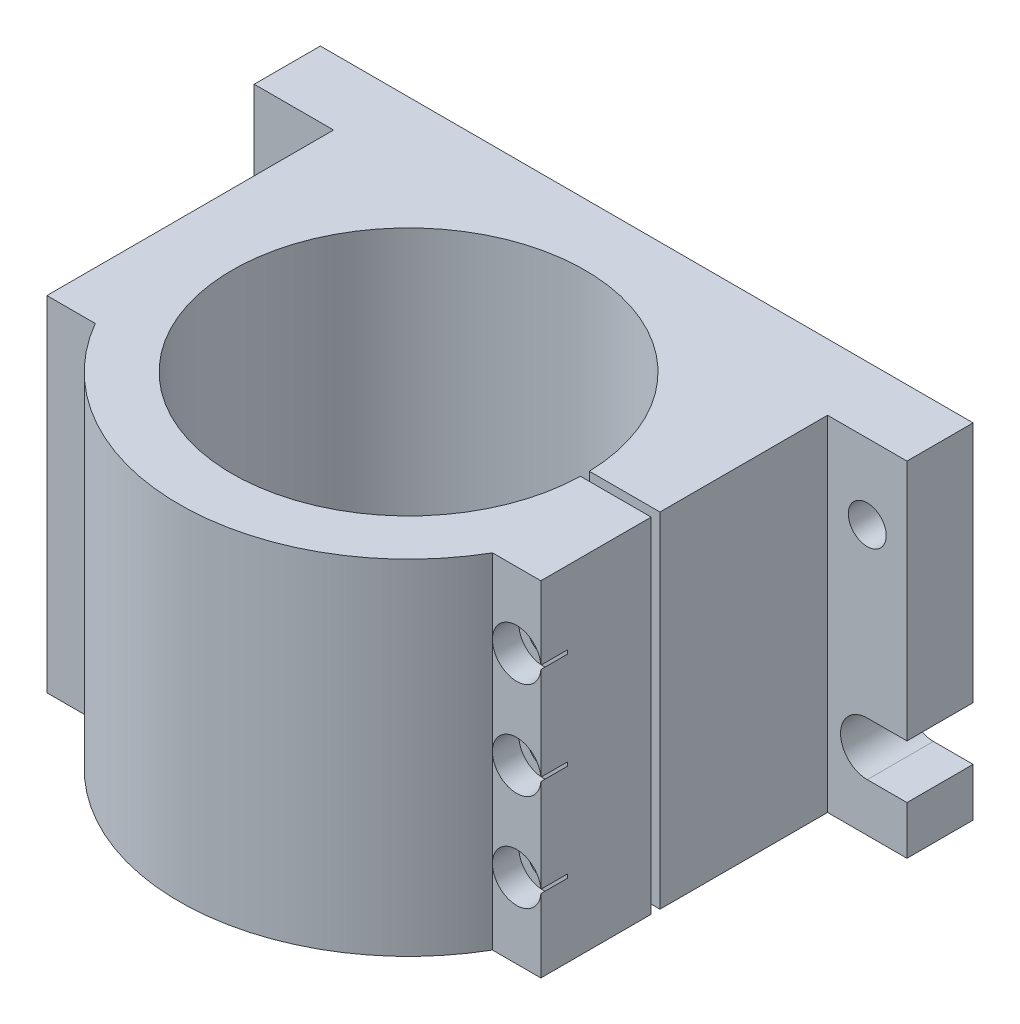
SolidWorks part; units mm, degrees
material "AA356.0-F"
ref_plane "Front Plane" through (0, 0, 0) normal (0, 0, 1) x (1, 0, 0)
ref_plane "Top Plane" through (0, 0, 0) normal (0, 1, 0) x (1, 0, 0)
ref_plane "Right Plane" through (0, 0, 0) normal (1, 0, 0) x (0, 0, -1)
sketch "Sketch1" plane through (0, 0, 0) normal (0, 1, 0) x (1, 0, 0)
  line L0 (-74, 54) -> (74, 54)
  line L1 (74, 54) -> (74, 39)
  line L2 (74, 39) -> (56, 39)
  line L3 (56, 39) -> (56, -26)
  line L4 (56, -26) -> (45.0333, -26)
  line L5 (-74, 54) -> (-74, 39)
  line L6 (-74, 39) -> (-56, 39)
  line L7 (-56, 39) -> (-56, -26)
  line L8 (-56, -26) -> (-45.0333, -26)
  circle A0 centre (0, 0) radius 40
  arc A1 (45.0333, -26) -> (-45.0333, -26) centre (0, 0) cw
  dimension "D1" = 80
  dimension "D2" = 148
  dimension "D3" = 106
  dimension "D4" = 54
  dimension "D5" = 18
  dimension "D6" = 65
  dimension "D7" = 15
extrude "Boss-Extrude1" add sketch "Sketch1" along normal mid plane 78
sketch "Sketch2" plane through (0, 0, 0) normal (0, 1, 0) x (1, 0, 0)
  line L0 (56, -26) -> (56, 39) construction
  line L1 (0, 1) -> (56, 1)
  line L2 (0, 1) -> (0, -1)
  line L3 (0, -1) -> (56, -1)
  line L4 (56, 1) -> (56, -1)
  dimension "D1" = 2
extrude "Cut-Extrude1" cut sketch "Sketch2" against normal up to next and the other way up to next
hole_wizard "CBORE for M6 SHCS1" positions "Sketch3" profile "Sketch4" counterbore size "M6" standard "ANSI Metric"
sketch "Sketch3" plane through (0, 0, 26) normal (0, 0, 1) x (1, 0, 0)
  line L0 (50.5167, 22) -> (50.5167, 0)
  line L1 (50.5167, 0) -> (50.5167, -22)
  line L3 (58.3, 0) -> (-58.3, 0) construction
  line L4 (45.0333, -39) -> (56, -39) construction
  point P1 (50.5167, 22)
  point P2 (50.5167, 0)
  point P3 (50.5167, -22)
  point P10 (50.5167, -39)
  dimension "D1" = 22
sketch "Sketch4" plane through (50.5167, 22, 26) normal (1, 0, 0) x (0, -1, 0)
  line L0 (0, 0) -> (0, 25)
  line L1 (0, 25) -> (3.3, 25)
  line L3 (3.3, 25) -> (3.3, 6)
  line L4 (3.3, 6) -> (5.5, 6)
  line L5 (5.5, 6) -> (5.5, 0)
  line L7 (5.5, 0) -> (0, 0)
  line L11 (0, -6.35) -> (0, 107.95) construction
  dimension "Thru Hole Dia." = 6.6
  dimension "Thru Hole Depth" = 25
  dimension "C'Bore Dia." = 11
  dimension "C'Bore Depth" = 6
sketch "Sketch5" plane through (0, 0, -39) normal (0, 0, 1) x (1, 0, 0)
  line L0 (65, -15.95) -> (74, -15.95)
  line L1 (65, 22) -> (-65, 22) construction
  line L2 (65, 22) -> (65, -22) construction
  line L3 (65, -22) -> (-65, -22) construction
  line L4 (-65, 22) -> (-65, -22) construction
  line L5 (65, 22) -> (-65, -22) construction
  line L6 (65, -22) -> (-65, 22) construction
  line L7 (74, 39) -> (74, -39) construction
  line L8 (74, -15.95) -> (74, -28.05)
  line L9 (74, -28.05) -> (65, -28.05)
  circle A0 centre (65, 22) radius 4.3
  circle A1 centre (-65, -22) radius 4.3
  circle A2 centre (-65, 22) radius 5.05
  arc A3 (65, -15.95) -> (65, -28.05) centre (65, -22) ccw
  point P0 (0, 0)
  dimension "D4" = 8.6
  dimension "D5" = 10.1
  dimension "D1" = 44
  dimension "D2" = 130
  dimension "D3" = 12.1
extrude "Cut-Extrude2" cut sketch "Sketch5" against normal up to next
